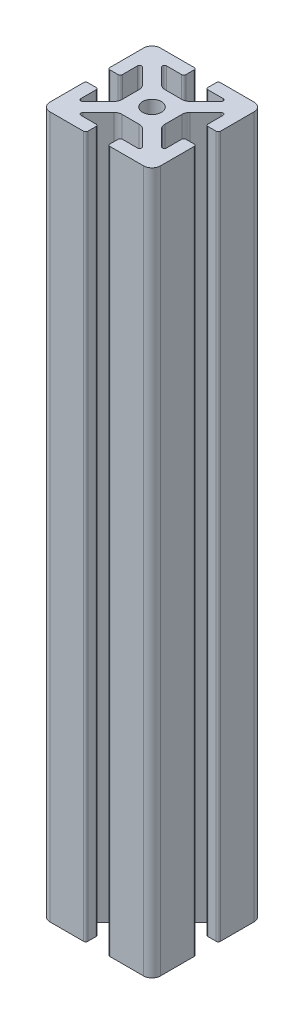
SolidWorks part; units mm, degrees
ref_plane "Front Plane" through (0, 0, 0) normal (0, 0, 1) x (1, 0, 0)
ref_plane "Top Plane" through (0, 0, 0) normal (0, 1, 0) x (1, 0, 0)
ref_plane "Right Plane" through (0, 0, 0) normal (1, 0, 0) x (0, 0, -1)
sketch "Sketch1" plane through (0, 0, 0) normal (0, 1, 0) x (1, 0, 0)
  line L2 (-20, 16.952) -> (-20, 4.7625)
  line L3 (-16.952, 20) -> (-4.7625, 20)
  line L4 (-4.0005, 19.238) -> (-4.0005, 16.2662)
  line L5 (-4.7625, 15.5042) -> (-10.2235, 15.5042)
  line L6 (-10.7623, 14.2034) -> (-5.194, 8.6351)
  line L7 (-14.2034, 10.7623) -> (-8.6351, 5.194)
  line L8 (-15.5042, 10.2235) -> (-15.5042, 4.7625)
  line L9 (-16.2662, 4.0005) -> (-19.238, 4.0005)
  line L11 (-3.0746, 7.7572) -> (3.0746, 7.7572)
  line L12 (-7.7572, 3.0746) -> (-7.7572, -3.0746)
  line L13 (16.2662, 4.0005) -> (19.238, 4.0005)
  line L14 (15.5042, 10.2235) -> (15.5042, 4.7625)
  line L15 (20, 16.952) -> (20, 4.7625)
  line L16 (16.952, 20) -> (4.7625, 20)
  line L17 (4.0005, 19.238) -> (4.0005, 16.2662)
  line L18 (4.7625, 15.5042) -> (10.2235, 15.5042)
  line L19 (7.7572, 3.0746) -> (7.7572, -3.0746)
  line L20 (10.7623, 14.2034) -> (5.194, 8.6351)
  line L21 (14.2034, 10.7623) -> (8.6351, 5.194)
  line L22 (-16.2662, -4.0005) -> (-19.238, -4.0005)
  line L23 (-15.5042, -10.2235) -> (-15.5042, -4.7625)
  line L24 (-14.2034, -10.7623) -> (-8.6351, -5.194)
  line L25 (-10.7623, -14.2034) -> (-5.194, -8.6351)
  line L26 (-4.7625, -15.5042) -> (-10.2235, -15.5042)
  line L27 (-4.0005, -19.238) -> (-4.0005, -16.2662)
  line L28 (-16.952, -20) -> (-4.7625, -20)
  line L29 (-20, -16.952) -> (-20, -4.7625)
  line L30 (20, -16.952) -> (20, -4.7625)
  line L31 (16.952, -20) -> (4.7625, -20)
  line L32 (4.0005, -19.238) -> (4.0005, -16.2662)
  line L33 (4.7625, -15.5042) -> (10.2235, -15.5042)
  line L34 (10.7623, -14.2034) -> (5.194, -8.6351)
  line L35 (14.2034, -10.7623) -> (8.6351, -5.194)
  line L36 (15.5042, -10.2235) -> (15.5042, -4.7625)
  line L37 (16.2662, -4.0005) -> (19.238, -4.0005)
  line L38 (-3.0746, -7.7572) -> (3.0746, -7.7572)
  circle A0 centre (0, 0) radius 3.4036
  arc A1 (-20, 16.952) -> (-16.952, 20) centre (-16.952, 16.952) cw
  arc A2 (-14.2034, 10.7623) -> (-15.5042, 10.2235) centre (-14.7422, 10.2235) ccw
  arc A3 (-10.2235, 15.5042) -> (-10.7623, 14.2034) centre (-10.2235, 14.7422) ccw
  arc A4 (-4.7625, 20) -> (-4.0005, 19.238) centre (-4.7625, 19.238) cw
  arc A5 (-20, 4.7625) -> (-19.238, 4.0005) centre (-19.238, 4.7625) ccw
  arc A6 (-15.5042, 4.7625) -> (-16.2662, 4.0005) centre (-16.2662, 4.7625) cw
  arc A7 (-4.0005, 16.2662) -> (-4.7625, 15.5042) centre (-4.7625, 16.2662) cw
  arc A8 (-3.0746, 7.7572) -> (-5.194, 8.6351) centre (-3.0746, 10.7544) cw
  arc A9 (-7.7572, 3.0746) -> (-8.6351, 5.194) centre (-10.7544, 3.0746) ccw
  arc A10 (15.5042, 4.7625) -> (16.2662, 4.0005) centre (16.2662, 4.7625) ccw
  arc A11 (20, 4.7625) -> (19.238, 4.0005) centre (19.238, 4.7625) cw
  arc A12 (20, 16.952) -> (16.952, 20) centre (16.952, 16.952) ccw
  arc A13 (4.7625, 20) -> (4.0005, 19.238) centre (4.7625, 19.238) ccw
  arc A14 (4.0005, 16.2662) -> (4.7625, 15.5042) centre (4.7625, 16.2662) ccw
  arc A15 (3.0746, 7.7572) -> (5.194, 8.6351) centre (3.0746, 10.7544) ccw
  arc A16 (7.7572, 3.0746) -> (8.6351, 5.194) centre (10.7544, 3.0746) cw
  arc A17 (14.2034, 10.7623) -> (15.5042, 10.2235) centre (14.7422, 10.2235) cw
  arc A18 (10.2235, 15.5042) -> (10.7623, 14.2034) centre (10.2235, 14.7422) cw
  arc A19 (-7.7572, -3.0746) -> (-8.6351, -5.194) centre (-10.7544, -3.0746) cw
  arc A20 (-3.0746, -7.7572) -> (-5.194, -8.6351) centre (-3.0746, -10.7544) ccw
  arc A21 (-4.0005, -16.2662) -> (-4.7625, -15.5042) centre (-4.7625, -16.2662) ccw
  arc A22 (-15.5042, -4.7625) -> (-16.2662, -4.0005) centre (-16.2662, -4.7625) ccw
  arc A23 (-20, -4.7625) -> (-19.238, -4.0005) centre (-19.238, -4.7625) cw
  arc A24 (-4.7625, -20) -> (-4.0005, -19.238) centre (-4.7625, -19.238) ccw
  arc A25 (-10.2235, -15.5042) -> (-10.7623, -14.2034) centre (-10.2235, -14.7422) cw
  arc A26 (-14.2034, -10.7623) -> (-15.5042, -10.2235) centre (-14.7422, -10.2235) cw
  arc A27 (-20, -16.952) -> (-16.952, -20) centre (-16.952, -16.952) ccw
  arc A28 (20, -16.952) -> (16.952, -20) centre (16.952, -16.952) cw
  arc A29 (14.2034, -10.7623) -> (15.5042, -10.2235) centre (14.7422, -10.2235) ccw
  arc A30 (10.2235, -15.5042) -> (10.7623, -14.2034) centre (10.2235, -14.7422) ccw
  arc A31 (4.7625, -20) -> (4.0005, -19.238) centre (4.7625, -19.238) cw
  arc A32 (20, -4.7625) -> (19.238, -4.0005) centre (19.238, -4.7625) ccw
  arc A33 (15.5042, -4.7625) -> (16.2662, -4.0005) centre (16.2662, -4.7625) cw
  arc A34 (4.0005, -16.2662) -> (4.7625, -15.5042) centre (4.7625, -16.2662) cw
  arc A35 (3.0746, -7.7572) -> (5.194, -8.6351) centre (3.0746, -10.7544) cw
  arc A36 (7.7572, -3.0746) -> (8.6351, -5.194) centre (10.7544, -3.0746) ccw
extrude "Boss-Extrude1" add sketch "Sketch1" along normal mid plane 254
